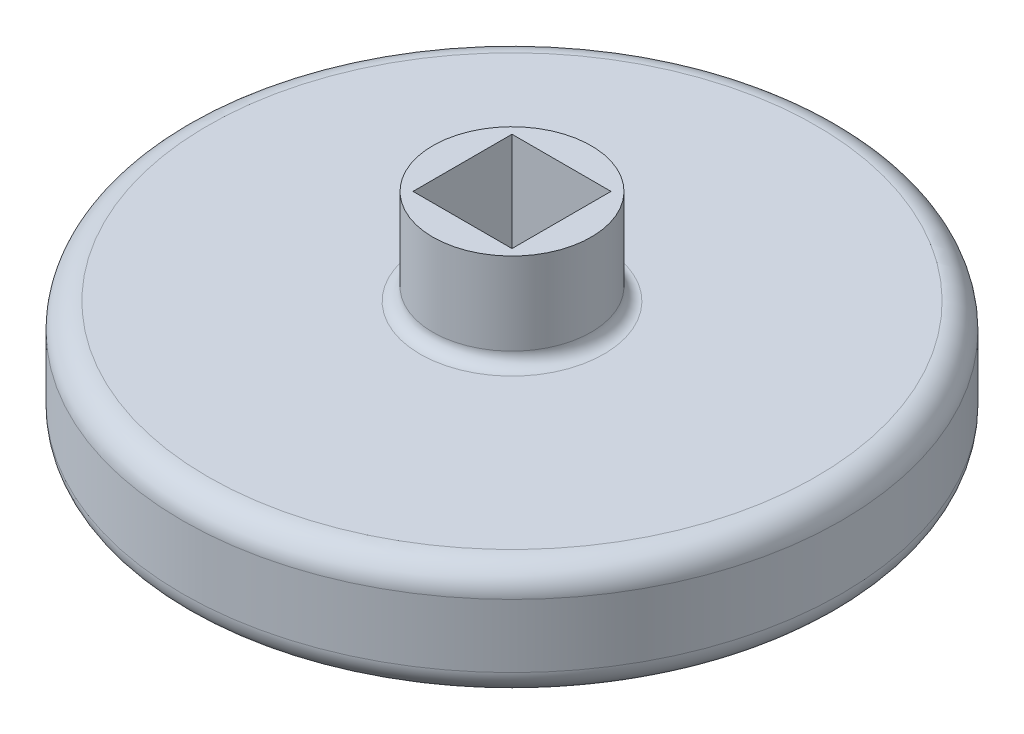
SolidWorks part; units mm, degrees
ref_plane "Front Plane" through (0, 0, 0) normal (0, 0, 1) x (1, 0, 0)
ref_plane "Top Plane" through (0, 0, 0) normal (0, 1, 0) x (1, 0, 0)
ref_plane "Right Plane" through (0, 0, 0) normal (1, 0, 0) x (0, 0, -1)
sketch "Sketch1" plane through (0, 0, 0) normal (0, 1, 0) x (1, 0, 0)
  circle A0 centre (0, 0) radius 33.02
  dimension "D1" = 66.04
extrude "Boss-Extrude1" add sketch "Sketch1" along normal blind 11.43
fillet "Fillet1" radius 2.54 2 edges at (0, 0, 33.02) (0, 11.43, 33.02)
sketch "Sketch3" plane through (0, 11.43, 0) normal (0, 1, 0) x (1, 0, 0)
  circle A0 centre (0, 0) radius 7.9375
  dimension "D1" = 15.875
extrude "Boss-Extrude2" add sketch "Sketch3" along normal blind 9.525 and the other way blind 20.955
fillet "Fillet2" radius 1.27 2 edges at (0, 0, 7.9375) (0, 11.43, 7.9375)
sketch "Sketch2" plane through (0, 11.43, 0) normal (0, 1, 0) x (1, 0, 0)
  line L1 (4.9609, -4.9609) -> (-4.9609, -4.9609)
  line L2 (4.9609, -4.9609) -> (4.9609, 4.9609)
  line L3 (4.9609, 4.9609) -> (-4.9609, 4.9609)
  line L4 (-4.9609, -4.9609) -> (-4.9609, 4.9609)
  line L5 (4.9609, -4.9609) -> (-4.9609, 4.9609) construction
  line L6 (4.9609, 4.9609) -> (-4.9609, -4.9609) construction
  point P0 (0, 0)
  dimension "D1" = 9.9219
  dimension "D2" = 9.9219
extrude "Cut-Extrude1" cut sketch "Sketch2" against normal through all both and the other way through all
